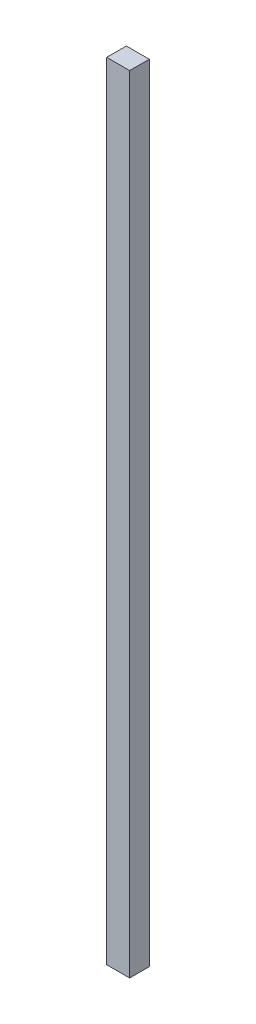
SolidWorks part; units mm, degrees
material "Balsa"
ref_plane "Front Plane" through (0, 0, 0) normal (1, 0, 0) x (0, 1, 0)
ref_plane "Top Plane" through (0, 0, 0) normal (0, 0, 1) x (0, 1, 0)
ref_plane "Right Plane" through (0, 0, 0) normal (0, 1, 0) x (-1, 0, 0)
sketch "Sketch1" plane through (0, 0, 0) normal (0, 0, 1) x (0, 1, 0)
  line L1 (60, 1.75) -> (-60, 1.75)
  line L2 (60, 1.75) -> (60, -1.75)
  line L3 (60, -1.75) -> (-60, -1.75)
  line L4 (-60, 1.75) -> (-60, -1.75)
  line L5 (60, 1.75) -> (-60, -1.75) construction
  line L6 (60, -1.75) -> (-60, 1.75) construction
  point P0 (0, 0)
  dimension "D1" = 3.5
  dimension "D2" = 120
extrude "Boss-Extrude1" add sketch "Sketch1" along normal blind 3
